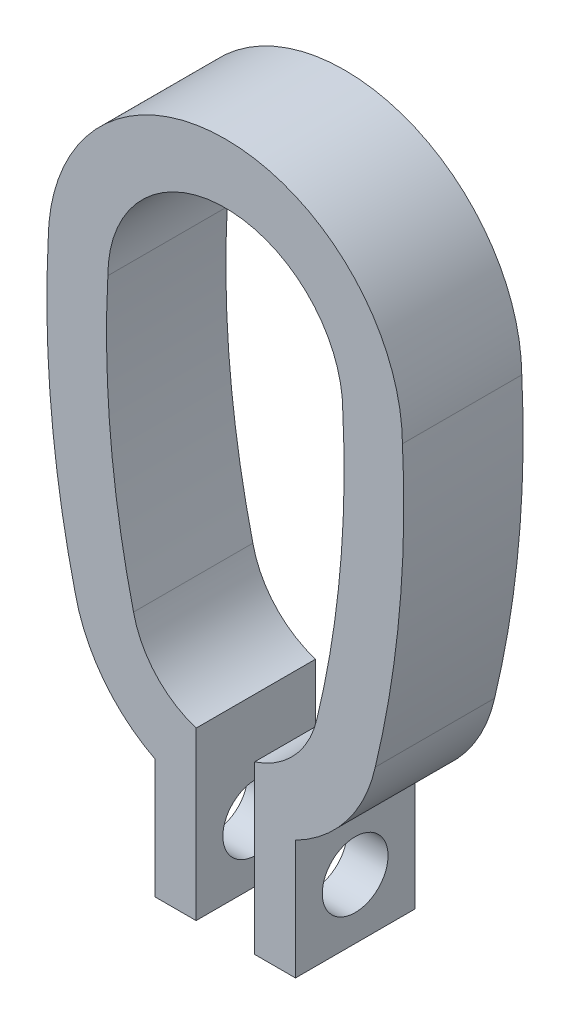
SolidWorks part; units mm, degrees
ref_plane "Front Plane" through (0, 0, 0) normal (0, 0, 1) x (1, 0, 0)
ref_plane "Top Plane" through (0, 0, 0) normal (0, 1, 0) x (1, 0, 0)
ref_plane "Right Plane" through (0, 0, 0) normal (1, 0, 0) x (0, 0, -1)
sketch "Sketch1" plane through (0, 0, 0) normal (0, 0, 1) x (1, 0, 0)
  line L3 (-3.1103, -37.004) -> (-3.1103, -54.7462)
  line L4 (-3.1103, -54.7462) -> (-7.4652, -54.7462)
  line L5 (-7.4652, -54.7462) -> (-7.4652, -42.0462)
  line L6 (3.1103, -37.004) -> (3.1103, -54.7462)
  line L7 (3.1103, -54.7462) -> (7.4652, -54.7462)
  line L8 (7.4652, -54.7462) -> (7.4652, -42.0462)
  arc A0 (12.5, 0) -> (-12.5, 0) centre (0, 0) ccw
  arc A1 (-9.7685, -29.6391) -> (-3.1103, -37.004) centre (0, -27.5) ccw
  arc A2 (-12.5, 0) -> (-9.7685, -29.6391) centre (91.0364, -5.4038) ccw
  arc A3 (12.5, 0) -> (9.7685, -29.6391) centre (-91.0364, -5.4038) cw
  arc A4 (18.8491, 0.1801) -> (-18.8491, 0.1801) centre (0, 0) ccw
  arc A5 (-18.8491, 0.1801) -> (-15.9561, -31.0673) centre (91.0364, -5.4038) ccw
  arc A6 (-15.9561, -31.0673) -> (-7.4652, -42.0462) centre (0, -27.5) ccw
  arc A7 (18.8491, 0.1801) -> (15.9561, -31.0673) centre (-91.0364, -5.4038) cw
  arc A8 (7.4652, -42.0462) -> (15.9561, -31.0673) centre (0, -27.5) ccw
  arc A9 (-15.9561, -31.0673) -> (15.9561, -31.0673) centre (0, -27.5) ccw construction
  arc A10 (3.1103, -37.004) -> (9.7685, -29.6391) centre (0, -27.5) ccw
  arc A11 (-9.7685, -29.6391) -> (9.7685, -29.6391) centre (0, -27.5) ccw construction
  dimension "D1" = 25
  dimension "D2" = 20
  dimension "D4" = 103.6773
  dimension "D5" = 6.35
extrude "Boss-Extrude1" add sketch "Sketch1" along normal blind 12.7
sketch "Sketch2" plane through (7.4652, 0, 0) normal (1, 0, 0) x (0, 0, -1)
  line L0 (0, -42.0462) -> (-12.7, -54.7462)
  line L1 (-12.7, -54.7462) -> (0, -54.7462) construction
  line L2 (-12.7, -54.7462) -> (-12.7, -42.0462) construction
  circle A0 centre (-6.35, -48.3962) radius 3.5
  dimension "D1" = 7
extrude "Cut-Extrude1" cut sketch "Sketch2" against normal blind 127 contours A0
